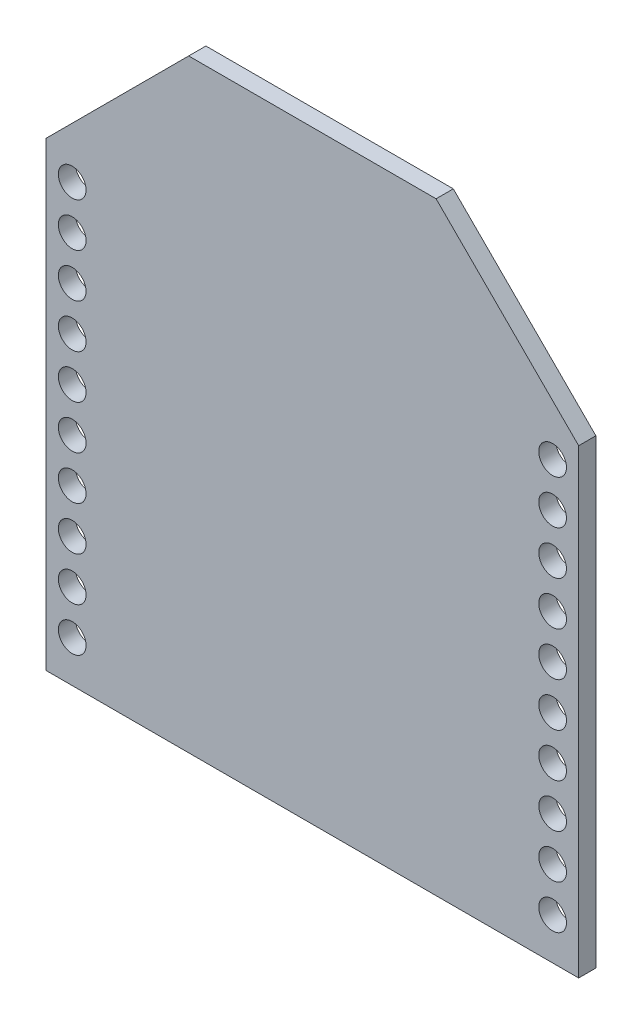
SolidWorks part; units mm, degrees
ref_plane "Alzado" through (0, 0, 0) normal (0, 0, 1) x (1, 0, 0)
ref_plane "Planta" through (0, 0, 0) normal (0, 1, 0) x (1, 0, 0)
ref_plane "Vista lateral" through (0, 0, 0) normal (1, 0, 0) x (0, 0, -1)
sketch "Croquis1" plane through (0, 0, 0) normal (0, 0, 1) x (1, 0, 0)
  line L0 (-5.6642, 13.8176) -> (-12.192, 7.2898)
  line L1 (12.192, -13.8176) -> (-12.192, -13.8176)
  line L2 (12.192, -13.8176) -> (12.192, 7.2898)
  line L3 (5.6642, 13.8176) -> (-5.6642, 13.8176)
  line L4 (-12.192, -13.8176) -> (-12.192, 7.2898)
  line L5 (12.192, -13.8176) -> (-12.192, 13.8176) construction
  line L6 (12.192, 13.8176) -> (-12.192, -13.8176) construction
  line L7 (12.192, 7.2898) -> (5.6642, 13.8176)
  line L8 (0, 13.8176) -> (0, -13.8176) construction
  line L9 (10.9982, -11.9126) -> (-10.9982, -11.9126) construction
  line L10 (-12.192, 0) -> (12.192, 0) construction
  circle A0 centre (-10.9982, -11.9126) radius 0.635
  circle A1 centre (10.9982, -11.9126) radius 0.635
  circle A2 centre (10.9982, -9.906) radius 0.635
  circle A3 centre (10.9982, -7.8994) radius 0.635
  circle A4 centre (10.9982, -5.8928) radius 0.635
  circle A5 centre (10.9982, -3.8862) radius 0.635
  circle A6 centre (10.9982, -1.8796) radius 0.635
  circle A7 centre (10.9982, 0.127) radius 0.635
  circle A8 centre (10.9982, 2.1336) radius 0.635
  circle A9 centre (10.9982, 4.1402) radius 0.635
  circle A10 centre (10.9982, 6.1468) radius 0.635
  circle A11 centre (-10.9982, -9.906) radius 0.635
  circle A12 centre (-10.9982, -7.8994) radius 0.635
  circle A13 centre (-10.9982, -5.8928) radius 0.635
  circle A14 centre (-10.9982, -3.8862) radius 0.635
  circle A15 centre (-10.9982, -1.8796) radius 0.635
  circle A16 centre (-10.9982, 0.127) radius 0.635
  circle A17 centre (-10.9982, 2.1336) radius 0.635
  circle A18 centre (-10.9982, 4.1402) radius 0.635
  circle A19 centre (-10.9982, 6.1468) radius 0.635
  point P0 (0, 0)
  point P15 (0, -11.9126)
  dimension "D7" = 1.27
  dimension "D8" = 2
  dimension "D10" = 2.0066
  dimension "D11" = 21.9964
  dimension "D1" = 24.384
  dimension "D2" = 13.8176
  dimension "D3" = 21.9964
  dimension "D4" = 11.9126
  dimension "D9" = 10
extrude "Saliente-Extruir1" add sketch "Croquis1" along normal blind 0.7874
